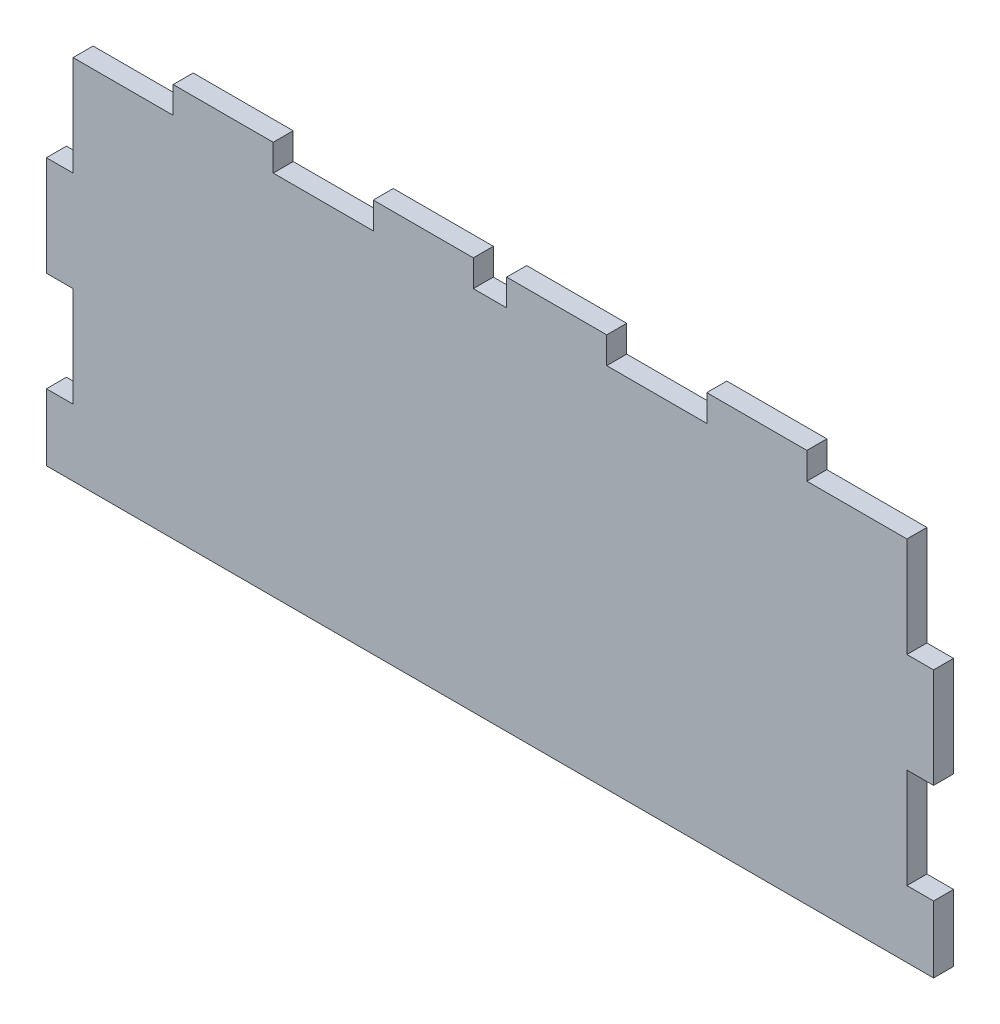
SolidWorks part; units mm, degrees
ref_plane "Front Plane" through (0, 0, 0) normal (0, 0, 1) x (1, 0, 0)
ref_plane "Top Plane" through (0, 0, 0) normal (0, 1, 0) x (1, 0, 0)
ref_plane "Right Plane" through (0, 0, 0) normal (1, 0, 0) x (0, 0, -1)
sketch "Sketch1" plane through (0, 0, 0) normal (0, 0, 1) x (1, 0, 0)
  line L1 (0, 0) -> (-125, 0)
  line L2 (0, 0) -> (0, 55)
  line L3 (0, 55) -> (-125, 55)
  line L4 (-125, 0) -> (-125, 55)
  dimension "D1" = 55
  dimension "D2" = 125
extrude "Boss-Extrude1" add sketch "Sketch1" along normal blind 3
sketch "Sketch2" plane through (0, 0, 3) normal (0, 0, 1) x (1, 0, 0)
  line L0 (-129, 10) -> (-129, 0)
  line L1 (-125, 10) -> (-125, 0)
  line L2 (-62.5, 55) -> (-62.5, 0) construction
  line L3 (0, 55) -> (-125, 55) construction
  line L4 (-125, 0) -> (0, 0) construction
  line L5 (0, 10) -> (4, 10)
  line L6 (0, 25) -> (4, 25)
  line L8 (-129, 55) -> (-129, 0)
  line L9 (-129, 40) -> (-129, 25)
  line L10 (-125, 40) -> (-125, 25)
  line L11 (-125, 0) -> (-129, 0)
  line L12 (-129, 40) -> (-125, 40)
  line L13 (-125, 25) -> (-129, 25)
  line L14 (-125, 10) -> (-129, 10)
  line L15 (4, 40) -> (0, 40)
  line L16 (0, 0) -> (4, 0)
  line L17 (0, 40) -> (0, 25)
  line L18 (4, 40) -> (4, 25)
  line L19 (0, 10) -> (0, 0)
  line L20 (4, 10) -> (4, 0)
  line L21 (-65, 59) -> (-80, 59)
  line L23 (0, 59) -> (-125, 59)
  line L24 (-15, 59) -> (-30, 59)
  line L26 (-110, 59) -> (-110, 55)
  line L27 (-95, 59) -> (-95, 55)
  line L28 (-80, 59) -> (-80, 55)
  line L29 (-65, 59) -> (-65, 55)
  line L30 (-45, 59) -> (-45, 55)
  line L31 (-30, 59) -> (-30, 55)
  line L32 (-15, 59) -> (-15, 55)
  line L33 (-110, 55) -> (-95, 55)
  line L34 (-60, 59) -> (-60, 55)
  line L35 (-60, 55) -> (-45, 55)
  line L36 (-95, 59) -> (-110, 59)
  line L37 (-80, 55) -> (-65, 55)
  line L38 (-45, 59) -> (-60, 59)
  line L39 (-30, 55) -> (-15, 55)
  dimension "D4" = 15
  dimension "D5" = 15
  dimension "D6" = 15
  dimension "D7" = 15
  dimension "D8" = 15
  dimension "D10" = 15
  dimension "D11" = 15
  dimension "D12" = 15
  dimension "D1" = 4
  dimension "D2" = 4
extrude "Boss-Extrude2" add sketch "Sketch2" against normal blind 3
